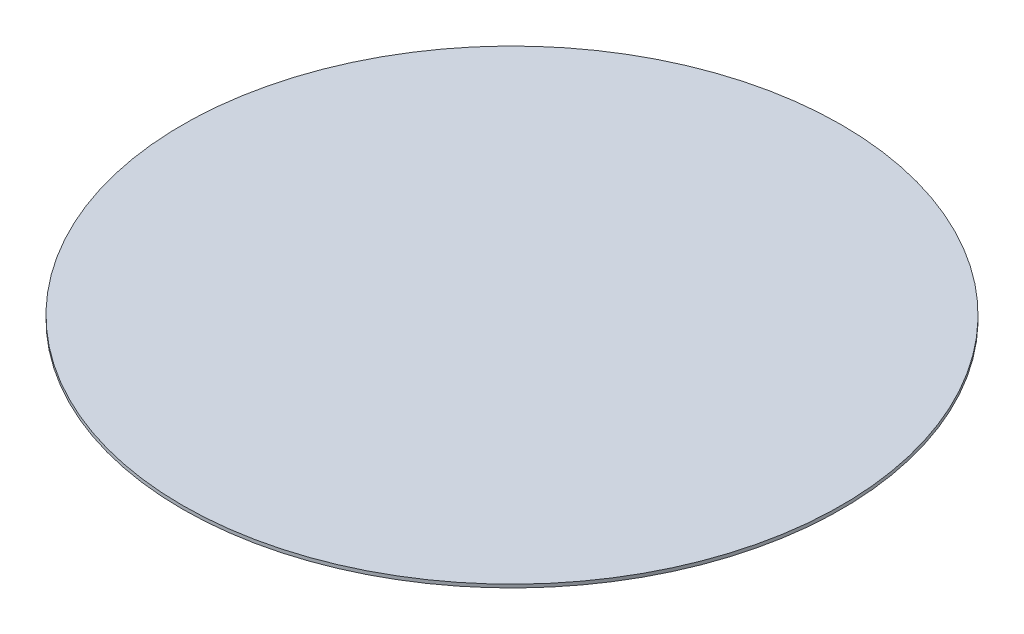
SolidWorks part; units mm, degrees
ref_plane "Front Plane" through (0, 0, 0) normal (0, 0, 1) x (1, 0, 0)
ref_plane "Top Plane" through (0, 0, 0) normal (0, 1, 0) x (1, 0, 0)
ref_plane "Right Plane" through (0, 0, 0) normal (1, 0, 0) x (0, 0, -1)
sketch "Sketch1" plane through (0, 0, 0) normal (0, 1, 0) x (1, 0, 0)
  circle A0 centre (0, 0) radius 100
  dimension "D1" = 200
extrude "Boss-Extrude1" add sketch "Sketch1" along normal blind 1
